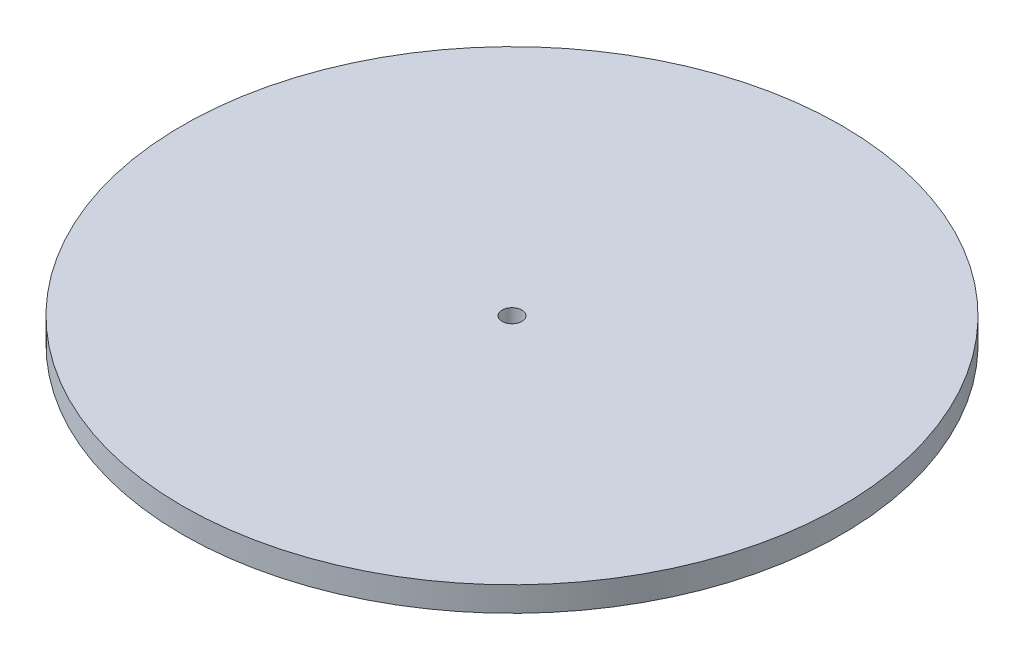
SolidWorks part; units mm, degrees
ref_plane "Front Plane" through (0, 0, 0) normal (0, 0, 1) x (1, 0, 0)
ref_plane "Top Plane" through (0, 0, 0) normal (0, 1, 0) x (1, 0, 0)
ref_plane "Right Plane" through (0, 0, 0) normal (1, 0, 0) x (0, 0, -1)
sketch "Sketch3" plane through (0, 0, 0) normal (0, 0, 1) x (1, 0, 0)
  line L0 (37, 6.823) -> (37, 10.823) construction
  line L1 (37, 10.823) -> (0, 10.823) construction
  line L2 (0, 10.823) -> (0, 0) construction
  line L4 (1.2, 10.823) -> (1.2, 5.823)
  line L5 (1.2, 5.823) -> (0, 5.823)
  line L6 (0, 5.823) -> (0, 0)
  line L7 (37, 6.823) -> (40, 6.823) construction
  line L8 (40, 6.823) -> (40, 10.823) construction
  line L9 (40, 10.823) -> (1.2, 10.823)
  line L10 (37, 6.823) -> (37, 7.823)
  line L11 (37, 7.823) -> (40, 7.823)
  line L12 (40, 7.823) -> (40, 10.823)
  spline S0 degree 8 poles (-3.7, 0.1129) (1.8454, -0.2134) (7.3907, -0.0687) (12.9361, 1.0886) (18.4814, 2.3051) (24.0268, 3.648) (29.5722, 5.0198) (35.1175, 6.3706) (40.6629, 7.71) knots 0 0 0 0 0 0 0 0 0 1 1 1 1 1 1 1 1 1 construction
  spline S1 degree 8 poles (0, 0) (4.625, 0.0011) (9.25, 0.4285) (13.875, 1.3243) (18.5, 2.3443) (23.125, 3.4409) (27.75, 4.5703) (32.375, 5.7002) (37, 6.823) knots 0.083403 0.083403 0.083403 0.083403 0.083403 0.083403 0.083403 0.083403 0.083403 0.917434 0.917434 0.917434 0.917434 0.917434 0.917434 0.917434 0.917434 0.917434
  dimension "D1" = 3
  dimension "D2" = 1.2
  dimension "D3" = 5
  dimension "D4" = 3
  dimension "D5" = 40
  dimension "D6" = 6.823
  dimension "D7" = 37
  dimension "D8" = 4
revolve "Revolve4" add sketch "Sketch3" angle 360 about L2
sketch "Sketch5" plane through (0, 10.823, 0) normal (0, 1, 0) x (1, 0, 0)
  circle A0 centre (0, 0) radius 1.2
  circle A2 centre (0, 0) radius 1.2 construction
extrude "Cut-Extrude1" cut sketch "Sketch5" against normal through all
